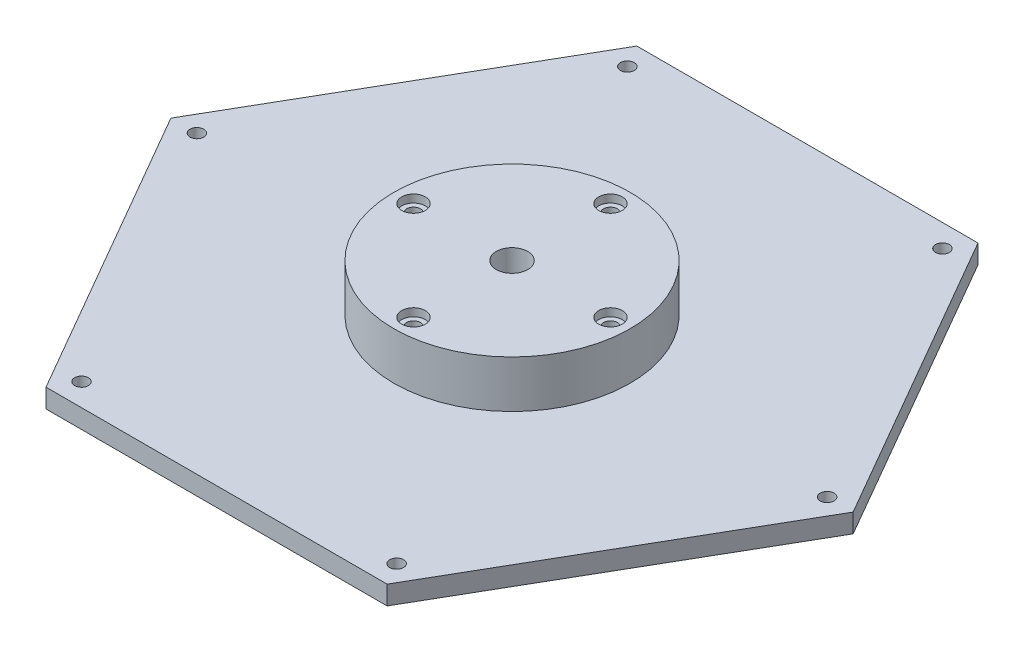
SolidWorks part; units mm, degrees
ref_plane "Front Plane" through (0, 0, 0) normal (0, 0, 1) x (1, 0, 0)
ref_plane "Top Plane" through (0, 0, 0) normal (0, 1, 0) x (1, 0, 0)
ref_plane "Right Plane" through (0, 0, 0) normal (1, 0, 0) x (0, 0, -1)
sketch "Sketch1" plane through (0, 0, 0) normal (0, 1, 0) x (1, 0, 0)
  line L38 (86.6025, 0) -> (43.3013, 75)
  line L39 (43.3013, 75) -> (-43.3013, 75)
  line L40 (-43.3013, 75) -> (-86.6025, 0)
  line L41 (-86.6025, 0) -> (-43.3013, -75)
  line L42 (-43.3013, -75) -> (43.3013, -75)
  line L43 (43.3013, -75) -> (86.6025, 0)
  circle A13 centre (0, 0) radius 75 construction
  circle A14 centre (0, 0) radius 4
  dimension "D2" = 8
  dimension "D1" = 150
extrude "Boss-Extrude2" add sketch "Sketch1" along normal blind 4.8
sketch "Sketch2" plane through (0, 4.8, 0) normal (0, 1, 0) x (1, 0, 0)
  circle A0 centre (0, 0) radius 4
  circle A1 centre (0, 0) radius 30
  dimension "D1" = 60
extrude "Boss-Extrude3" add sketch "Sketch2" along normal blind 12
sketch "Sketch3" plane through (0, 16.8, 0) normal (0, 1, 0) x (1, 0, 0)
  line L0 (0, 0) -> (25, 0) construction
  line L1 (0, 0) -> (43.3013, 75) construction
  line L2 (0, 0) -> (40, 69.282) construction
  circle A0 centre (25, 0) radius 1.75
  circle A1 centre (0, -25) radius 1.75
  circle A2 centre (-25, 0) radius 1.75
  circle A3 centre (0, 25) radius 1.75
  circle A4 centre (40, 69.282) radius 1.75
  circle A5 centre (80, 0) radius 1.75
  circle A6 centre (40, -69.282) radius 1.75
  circle A7 centre (-40, -69.282) radius 1.75
  circle A8 centre (-80, 0) radius 1.75
  circle A9 centre (-40, 69.282) radius 1.75
  point P13 (0, 0)
  point P27 (0, 0)
  dimension "D2" = 3.5
  dimension "D5" = 3.5
  dimension "D1" = 25
  dimension "D4" = 80
  dimension "D3" = 4
  dimension "D6" = 6
extrude "Cut-Extrude1" cut sketch "Sketch3" against normal up to surface (16.8 mm away) up to face at (0, 0, 0)
sketch "Sketch4" plane through (0, 16.8, 0) normal (0, 1, 0) x (1, 0, 0)
  circle A0 centre (0, 25) radius 3
  circle A1 centre (25, 0) radius 3
  circle A2 centre (0, -25) radius 3
  circle A3 centre (-25, 0) radius 3
  point P12 (0, 0)
  dimension "D1" = 6
  dimension "D2" = 4
extrude "Cut-Extrude2" cut sketch "Sketch4" against normal blind 2
